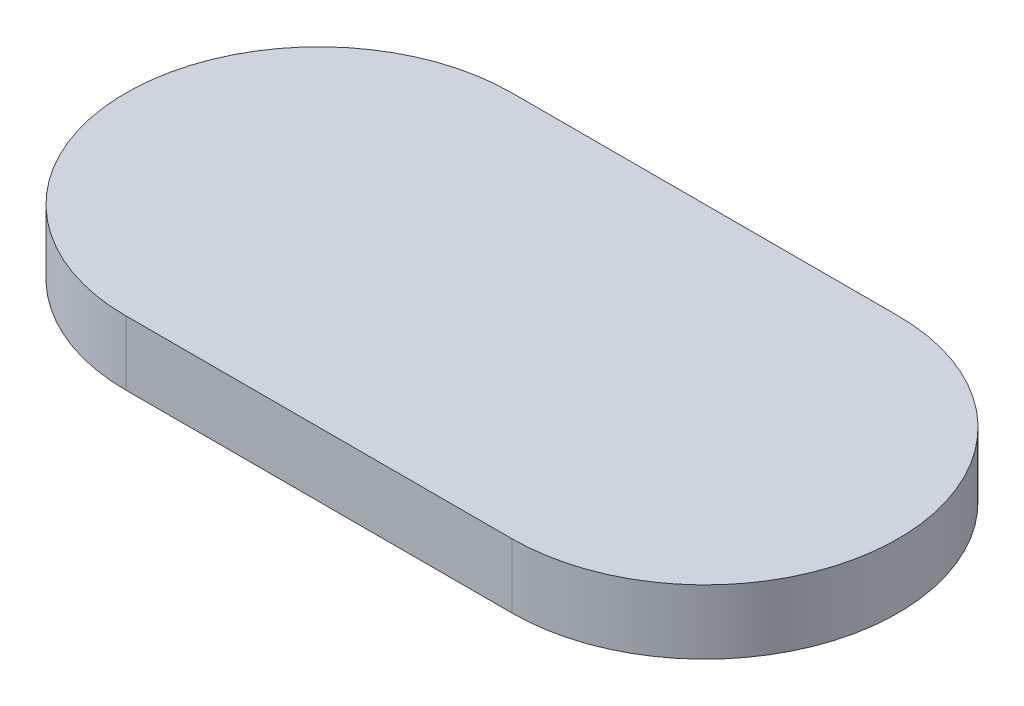
SolidWorks part; units mm, degrees
ref_plane "前视基准面" through (0, 0, 0) normal (0, 0, 1) x (1, 0, 0)
ref_plane "上视基准面" through (0, 0, 0) normal (0, 1, 0) x (1, 0, 0)
ref_plane "右视基准面" through (0, 0, 0) normal (1, 0, 0) x (0, 0, -1)
other "Configuration Table"
sketch "草图1" plane through (0, 0, 0) normal (0, 1, 0) x (1, 0, 0)
  line L0 (0, 0) -> (30, 0) construction
  line L1 (0, 15) -> (30, 15)
  line L2 (0, -15) -> (30, -15)
  arc A0 (0, 15) -> (0, -15) centre (0, 0) ccw
  arc A1 (30, -15) -> (30, 15) centre (30, 0) ccw
  point P3 (15, 0)
  dimension "D1" = 30
  dimension "D2" = 15
extrude "凸台-拉伸1" add sketch "草图1" along normal blind 5
sketch "草图2" plane through (0, 0, 0) normal (0, -1, 0) x (1, 0, 0)
  circle A0 centre (0, 0) radius 2.5
  dimension "D1" = 5
extrude "凸台-拉伸2" add sketch "草图2" along normal blind 5
